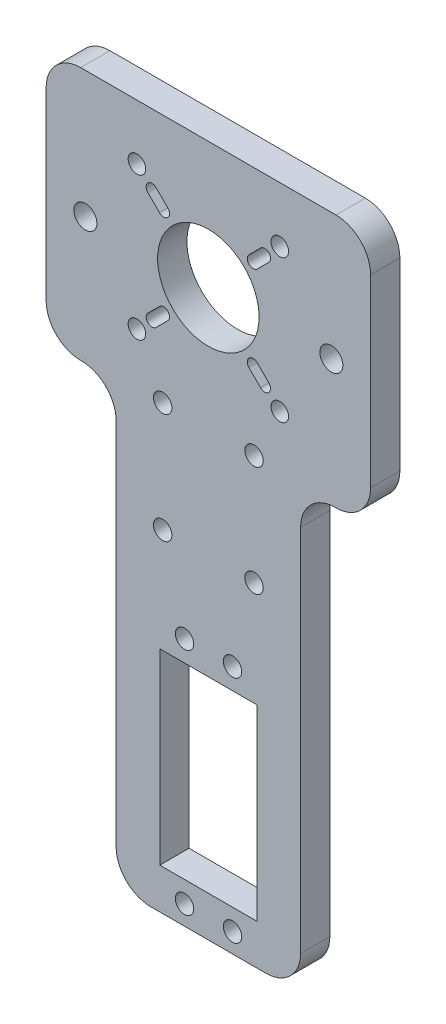
SolidWorks part; units mm, degrees
ref_plane "Front Plane" through (0, 0, 0) normal (0, 0, 1) x (1, 0, 0)
ref_plane "Top Plane" through (0, 0, 0) normal (0, 1, 0) x (1, 0, 0)
ref_plane "Right Plane" through (0, 0, 0) normal (1, 0, 0) x (0, 0, -1)
sketch "Sketch1" plane through (0, 0, 0) normal (0, 0, 1) x (1, 0, 0)
  line L0 (0, 0) -> (0, 11.938) construction
  line L3 (-20, -84) -> (20, -84)
  line L5 (-21.209, 78.74) -> (21.209, -78.74) construction
  line L6 (-21.209, -78.74) -> (21.209, 78.74) construction
  line L7 (0, 11.938) -> (9.906, 11.938) construction
  line L8 (0, 0) -> (0, 38.5) construction
  line L9 (0, 38.5) -> (15.494, 38.5) construction
  line L10 (15.494, 38.5) -> (15.494, 53.994) construction
  line L11 (0, 38.5) -> (10.9602, 49.4602) construction
  line L12 (9.7029, 48.2029) -> (12.2174, 50.7174) construction
  line L13 (8.8049, 49.1009) -> (11.3194, 51.6154)
  line L14 (10.6009, 47.3049) -> (13.1154, 49.8194)
  line L17 (9.7029, 28.7971) -> (12.2174, 26.2826) construction
  line L24 (0, 0) -> (0, -30) construction
  line L25 (0, -30) -> (-5.1689, -30) construction
  line L26 (0, -30) -> (0, -54.892) construction
  line L27 (0, 38.5) -> (-26.67, 38.5) construction
  line L28 (-10.541, -34.572) -> (10.541, -34.572)
  line L29 (-10.541, -34.572) -> (-10.541, -75.212)
  line L30 (-10.541, -75.212) -> (10.541, -75.212)
  line L31 (10.541, -34.572) -> (10.541, -75.212)
  line L32 (-10.541, -34.572) -> (10.541, -75.212) construction
  line L33 (-10.541, -75.212) -> (10.541, -34.572) construction
  line L40 (-20, 11) -> (-20, -84)
  line L41 (-35.179, 11) -> (-20, 11)
  line L42 (-35.179, 11) -> (-35.179, 66)
  line L43 (-35.179, 66) -> (35.179, 66)
  line L44 (35.179, 11) -> (35.179, 66)
  line L45 (-35.179, 11) -> (35.179, 66) construction
  line L46 (-35.179, 66) -> (35.179, 11) construction
  line L47 (20, 11) -> (20, -84)
  line L48 (20, 11) -> (35.179, 11)
  line L67 (10.6009, 29.6951) -> (13.1154, 27.1806)
  line L70 (8.8049, 27.8991) -> (11.3194, 25.3846)
  line L73 (-9.7029, 28.7971) -> (-12.2174, 26.2826) construction
  line L74 (-8.8049, 27.8991) -> (-11.3194, 25.3846)
  line L75 (-10.6009, 29.6951) -> (-13.1154, 27.1806)
  line L76 (-9.7029, 48.2029) -> (-12.2174, 50.7174) construction
  line L77 (-10.6009, 47.3049) -> (-13.1154, 49.8194)
  line L78 (-8.8049, 49.1009) -> (-11.3194, 51.6154)
  circle A0 centre (9.906, 11.938) radius 2
  circle A1 centre (-9.906, 11.938) radius 2
  circle A2 centre (-9.906, -11.938) radius 2
  circle A3 centre (9.906, -11.938) radius 2
  circle A4 centre (0, 38.5) radius 11
  circle A5 centre (15.494, 53.994) radius 1.905
  arc A9 (8.8049, 49.1009) -> (10.6009, 47.3049) centre (9.7029, 48.2029) ccw
  arc A10 (13.1154, 49.8194) -> (11.3194, 51.6154) centre (12.2174, 50.7174) ccw
  circle A17 centre (-5.1689, -30) radius 2
  circle A18 centre (5.2451, -30) radius 2
  circle A19 centre (5.2451, -79.784) radius 2
  circle A20 centre (-5.1689, -79.784) radius 2
  circle A21 centre (-26.67, 38.5) radius 2.5
  circle A28 centre (26.67, 38.5) radius 2.5
  circle A73 centre (15.494, 23.006) radius 1.905
  arc A74 (10.6009, 29.6951) -> (8.8049, 27.8991) centre (9.7029, 28.7971) ccw
  arc A75 (11.3194, 25.3846) -> (13.1154, 27.1806) centre (12.2174, 26.2826) ccw
  circle A76 centre (-15.494, 23.006) radius 1.905
  arc A77 (-8.8049, 27.8991) -> (-10.6009, 29.6951) centre (-9.7029, 28.7971) ccw
  arc A78 (-13.1154, 27.1806) -> (-11.3194, 25.3846) centre (-12.2174, 26.2826) ccw
  circle A79 centre (-15.494, 53.994) radius 1.905
  arc A80 (-10.6009, 47.3049) -> (-8.8049, 49.1009) centre (-9.7029, 48.2029) ccw
  arc A81 (-11.3194, 51.6154) -> (-13.1154, 49.8194) centre (-12.2174, 50.7174) ccw
  point P0 (0, 0)
  point P30 (10.9602, 49.4602)
  point P39 (10.9602, 27.5398)
  point P48 (-10.9602, 27.5398)
  point P57 (-10.9602, 49.4602)
  point P76 (0, 38.5)
  point P83 (-27.5895, 11)
  dimension "D3" = 4
  dimension "D6" = 22
  dimension "D9" = 3.81
  dimension "D15" = 1.27
  dimension "D27" = 4
  dimension "D30" = 5
  dimension "D11" = 55
  dimension "D31" = 9.906
  dimension "D1" = 11.938
  dimension "D2" = 9.906
  dimension "D5" = 38.5
  dimension "D7" = 15.494
  dimension "D8" = 15.494
  dimension "D13" = 95
  dimension "D14" = 45
  dimension "D16" = 1.778
  dimension "D17" = 15.5
  dimension "D19" = 30
  dimension "D20" = 5.1689
  dimension "D23" = 24.892
  dimension "D24" = 40.64
  dimension "D25" = 21.082
  dimension "D28" = 70.358
  dimension "D29" = 26.67
  dimension "D32" = 11.938
  dimension "D12" = 40
  dimension "D26" = 2
  dimension "D4" = 2
  dimension "D21" = 2
  dimension "D22" = 2
  dimension "D10" = 4
extrude "Boss-Extrude1" add sketch "Sketch1" along normal mid plane 6.35 contours A20 L3 A19 L47 L48 L44 L43 L42 L41 L40 A81 L78 A80 L77 A79 A78 L75 A77 L74 A76 A75 L70 A74 L67 A73 L28 L31 L30 L29 A0 A1 A2 A3 A4 A5
fillet "Fillet1" radius 7.5 8 edges at (-20, -84, 0) (20, -84, 0) (20, 11, 0) (35.179, 11, 0) (35.179, 66, 0) (-20, 11, 0) (-35.179, 11, 0) (-35.179, 66, 0)
